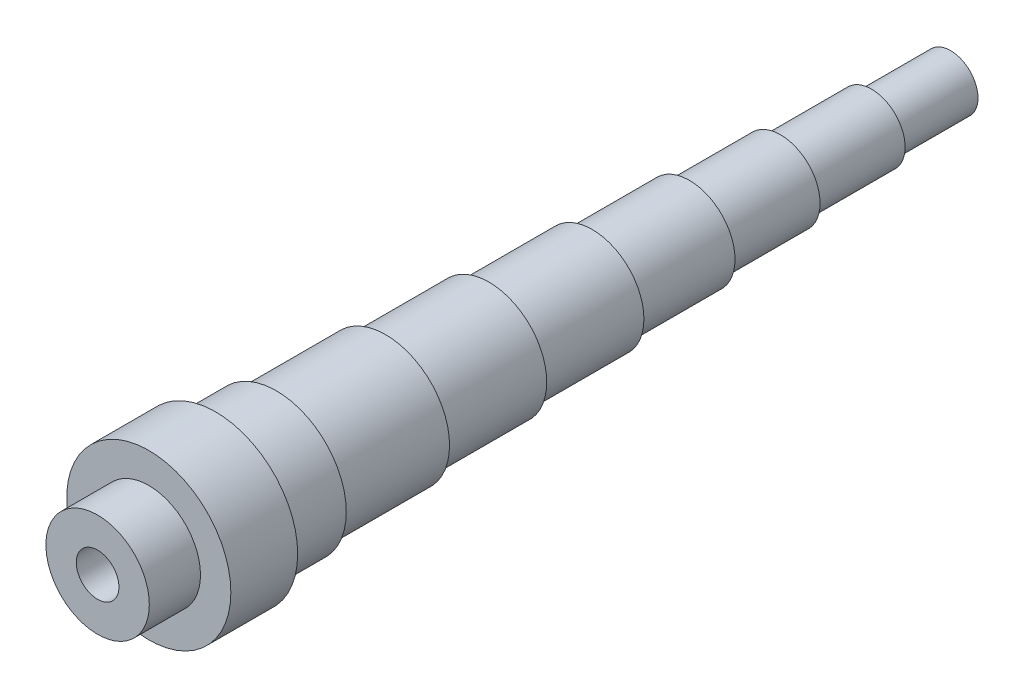
SolidWorks part; units mm, degrees
material "Copper"
ref_plane "Front Plane" through (0, 0, 0) normal (0, 0, 1) x (1, 0, 0)
ref_plane "Top Plane" through (0, 0, 0) normal (0, 1, 0) x (1, 0, 0)
ref_plane "Right Plane" through (0, 0, 0) normal (1, 0, 0) x (0, 0, -1)
sketch "Sketch1" plane through (0, 0, 0) normal (1, 0, 0) x (0, 0, -1)
  line L0 (-19.9049, 0) -> (31.5847, 0) construction
  line L1 (-264.0381, 12.7) -> (213.4006, 12.7)
  line L2 (213.4006, 12.7) -> (213.4006, 16.317)
  line L3 (213.4006, 16.317) -> (166.3802, 16.317)
  line L4 (166.3802, 16.317) -> (166.3802, 19.9339)
  line L5 (166.3802, 19.9339) -> (112.1258, 19.9339)
  line L6 (112.1258, 19.9339) -> (112.1258, 23.5509)
  line L7 (112.1258, 23.5509) -> (57.8714, 23.5509)
  line L8 (57.8714, 23.5509) -> (57.8714, 27.1678)
  line L9 (57.8714, 27.1678) -> (0, 27.1678)
  line L10 (0, 27.1678) -> (0, 30.7848)
  line L11 (0, 30.7848) -> (-61.4883, 30.7848)
  line L12 (-61.4883, 30.7848) -> (-61.4883, 34.4018)
  line L13 (-61.4883, 34.4018) -> (-122.9766, 34.4018)
  line L14 (-122.9766, 34.4018) -> (-122.9766, 38.0187)
  line L15 (-122.9766, 38.0187) -> (-188.0819, 38.0187)
  line L16 (-264.0381, 38.0187) -> (-264.0381, 30.7848)
  line L17 (-188.0819, 38.0187) -> (-188.0819, 41.6357)
  line L18 (-188.0819, 41.6357) -> (-224.2515, 41.6357)
  line L19 (-224.2515, 41.6357) -> (-224.2515, 48.8696)
  line L20 (-264.0381, 38.0187) -> (-264.0381, 48.8696)
  line L21 (-264.0381, 48.8696) -> (-224.2515, 48.8696)
  line L22 (-264.0381, 30.7848) -> (-294.5181, 30.7848)
  line L23 (-294.5181, 30.7848) -> (-294.5181, 12.7)
  line L24 (-294.5181, 12.7) -> (-264.0381, 12.7)
  dimension "D1" = 12.7
  dimension "D2" = 477.4387
  dimension "D3" = 3.617
  dimension "D4" = 3.617
  dimension "D5" = 3.617
  dimension "D6" = 3.617
  dimension "D7" = 3.617
  dimension "D8" = 3.617
  dimension "D9" = 3.617
  dimension "D10" = 430.4182
  dimension "D11" = 376.1638
  dimension "D12" = 321.9094
  dimension "D13" = 264.0381
  dimension "D14" = 202.5498
  dimension "D15" = 3.617
  dimension "D16" = 7.2339
  dimension "D17" = 141.0614
  dimension "D18" = 75.9562
  dimension "D19" = 39.7866
  dimension "D20" = 30.48
revolve "Revolve1" add sketch "Sketch1" angle 360 about L0
